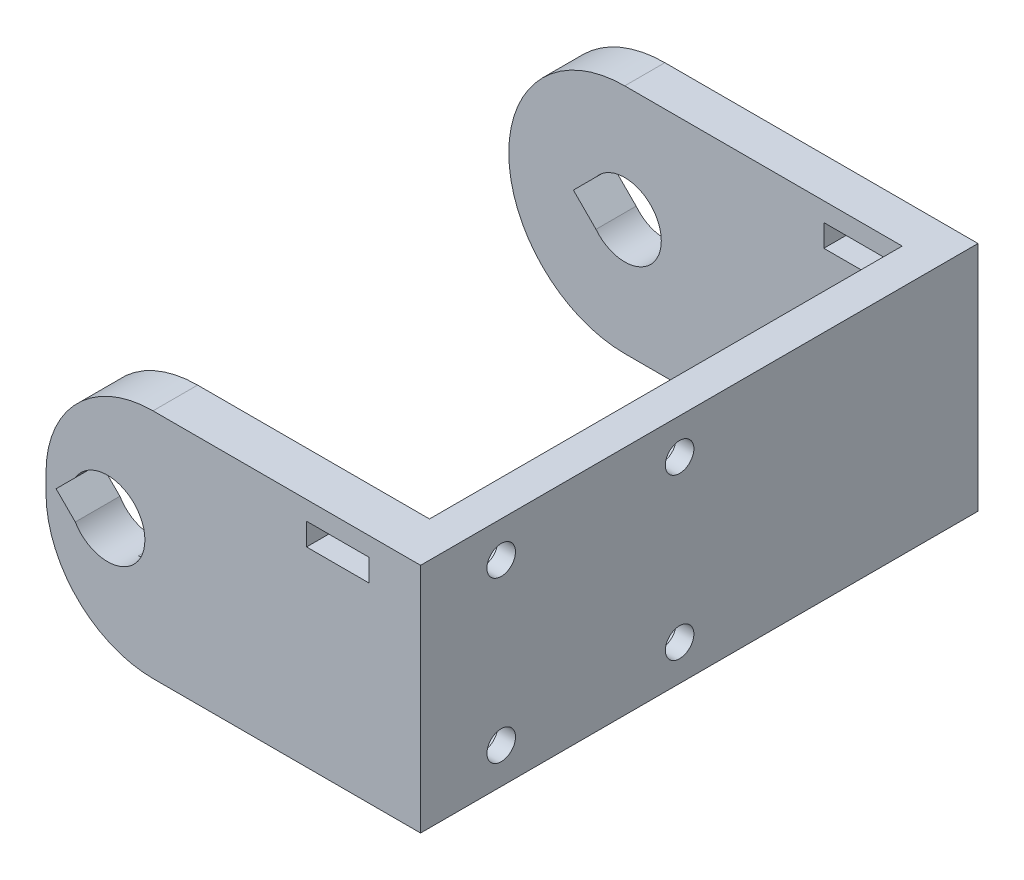
SolidWorks part; units mm, degrees
ref_plane "Front Plane" through (0, 0, 0) normal (0, 0, 1) x (1, 0, 0)
ref_plane "Top Plane" through (0, 0, 0) normal (0, 1, 0) x (1, 0, 0)
ref_plane "Right Plane" through (0, 0, 0) normal (1, 0, 0) x (0, 0, -1)
sketch "Sketch1" plane through (0, 0, 0) normal (0, 0, 1) x (1, 0, 0)
  line L0 (58.8, 0) -> (58.8, 13) construction
  line L1 (58.8, 13) -> (93.911, 13)
  line L2 (93.911, 13) -> (93.911, -13)
  line L3 (93.911, -13) -> (58.8, -13)
  circle A0 centre (58.8, 0) radius 4.1
  arc A1 (58.8, 13) -> (58.8, -13) centre (58.8, 0) ccw
extrude "Boss-Extrude1" add sketch "Sketch1" along normal blind 4.5
sketch "Sketch2" plane through (0, 0, 4.5) normal (0, 0, 1) x (1, 0, 0)
  line L0 (58.8, -13) -> (93.911, -13) construction
  line L1 (93.911, 13) -> (89.911, 13)
  line L2 (93.911, 13) -> (93.911, -13)
  line L3 (93.911, -13) -> (89.911, -13)
  line L4 (89.911, 13) -> (89.911, -13)
  dimension "D1" = 4
extrude "Boss-Extrude2" add sketch "Sketch2" along normal blind 58
sketch "Sketch3" plane through (89.911, 0, 0) normal (-1, 0, 0) x (0, 0, 1)
  line L0 (62.5, -13) -> (4.5, -13) construction
  line L1 (62.5, 13) -> (57.5, 13)
  line L2 (62.5, 13) -> (62.5, -13)
  line L3 (62.5, -13) -> (57.5, -13)
  line L4 (57.5, 13) -> (57.5, -13)
  dimension "D1" = 5
extrude "Boss-Extrude3" add sketch "Sketch3" along normal blind 38
sketch "Sketch5" plane through (0, 0, 62.5) normal (0, 0, 1) x (1, 0, 0)
  line L1 (75.8, 1.8) -> (59.9258, 3.9944)
  line L2 (59.9257, -3.9944) -> (75.8, -1.8)
  arc A0 (59.9258, 3.9944) -> (59.9257, -3.9944) centre (58.8, 0) ccw
  arc A1 (75.8, -1.8) -> (75.8, 1.8) centre (75.8, 0) ccw
  dimension "D1" = 17
extrude "Cut-Extrude1" cut sketch "Sketch5" along normal blind 3 from surface at -5 starting at face at (70.911, 0, 57.5)
sketch "Sketch6" plane through (0, 0, 62.5) normal (0, 0, 1) x (1, 0, 0)
  circle A0 centre (58.8, 0) radius 4.2
extrude "Cut-Extrude2" cut sketch "Sketch6" against normal blind 10
fillet "Fillet1" radius 12 2 edges at (51.911, 13, 60) (51.911, -13, 60)
sketch "Sketch7" plane through (0, 0, 0) normal (0, 0, -1) x (-1, 0, 0)
  line L0 (-56.2624, -3.2204) -> (-56.2624, 3.2204)
  line L1 (-53.0421, 0) -> (-56.2624, 3.2204)
  line L2 (-93.911, -13) -> (-93.911, 13) construction
  line L3 (-53.0421, 0) -> (-56.2624, -3.2204)
  circle A0 centre (-58.8, 0) radius 4.1 construction
  dimension "D1" = 45
extrude "Cut-Extrude4" cut sketch "Sketch7" against normal blind 74
sketch "Sketch8" plane through (93.911, 0, 0) normal (1, 0, 0) x (0, 0, -1)
  circle A0 centre (-53.4588, -8.9852) radius 1.6
  circle A1 centre (-53.4588, 9) radius 1.6
  circle A2 centre (-33.4588, 9) radius 1.6
  circle A3 centre (-33.4588, -8.9852) radius 1.6
  ellipse E0 centre (-53.4588, -8.9852) end of major axis (-55.0588, -8.9852) minor radius 1.6 (-51.8588, -8.9926) -> (-55.0588, -8.9926) ccw construction
  ellipse E1 centre (-33.4588, -8.9852) end of major axis (-31.8588, -8.9852) minor radius 1.6 (-31.8588, -8.9926) -> (-35.0588, -8.9926) ccw construction
extrude "Cut-Extrude5" cut sketch "Sketch8" against normal blind 8.5
sketch "Sketch9" plane through (89.911, 0, 0) normal (-1, 0, 0) x (0, 0, 1)
  line L1 (30.5878, -7.3766) -> (30.6302, -10.6672)
  line L2 (30.6302, -10.6672) -> (33.5012, -12.2758)
  line L3 (33.5012, -12.2758) -> (36.3297, -10.5938)
  line L4 (36.3297, -10.5938) -> (36.2874, -7.3032)
  line L5 (36.2874, -7.3032) -> (33.4164, -5.6946)
  line L6 (33.4164, -5.6946) -> (30.5878, -7.3766)
  line L7 (30.5842, 10.602) -> (30.6341, 7.3115)
  line L8 (30.6341, 7.3115) -> (33.5087, 5.7095)
  line L9 (33.5087, 5.7095) -> (36.3334, 7.398)
  line L10 (36.3334, 7.398) -> (36.2835, 10.6885)
  line L11 (36.2835, 10.6885) -> (33.4089, 12.2905)
  line L12 (33.4089, 12.2905) -> (30.5842, 10.602)
  line L13 (50.5892, -7.3742) -> (50.6288, -10.6649)
  line L14 (50.6288, -10.6649) -> (53.4984, -12.2759)
  line L15 (53.4984, -12.2759) -> (56.3284, -10.5962)
  line L16 (56.3284, -10.5962) -> (56.2888, -7.3056)
  line L17 (56.2888, -7.3056) -> (53.4192, -5.6946)
  line L18 (53.4192, -5.6946) -> (50.5892, -7.3742)
  line L19 (50.6928, 7.2169) -> (53.62, 5.7131)
  line L20 (53.62, 5.7131) -> (56.386, 7.4961)
  line L21 (56.386, 7.4961) -> (56.2248, 10.7831)
  line L22 (56.2248, 10.7831) -> (53.2976, 12.2869)
  line L23 (53.2976, 12.2869) -> (50.5316, 10.5039)
  line L24 (50.5316, 10.5039) -> (50.6928, 7.2169)
  circle A0 centre (33.4588, -8.9852) radius 2.85 construction
  circle A1 centre (33.4588, 9) radius 2.85 construction
  circle A2 centre (53.4588, -8.9852) radius 2.85 construction
  circle A3 centre (53.4588, 9) radius 2.85 construction
  dimension "D1" = 5.7
  dimension "D2" = 5.7
  dimension "D3" = 5.7
  dimension "D4" = 5.7
extrude "Cut-Extrude6" cut sketch "Sketch9" against normal blind 2
sketch "Sketch10" plane through (0, 0, 0) normal (0, 0, -1) x (-1, 0, 0)
  line L1 (-88.1249, 10.8892) -> (-81.1249, 10.8892)
  line L2 (-88.1249, 10.8892) -> (-88.1249, 8.3892)
  line L3 (-88.1249, 8.3892) -> (-81.1249, 8.3892)
  line L4 (-81.1249, 10.8892) -> (-81.1249, 8.3892)
  dimension "D1" = 7
  dimension "D2" = 2.5
extrude "Cut-Extrude7" cut sketch "Sketch10" against normal blind 114
